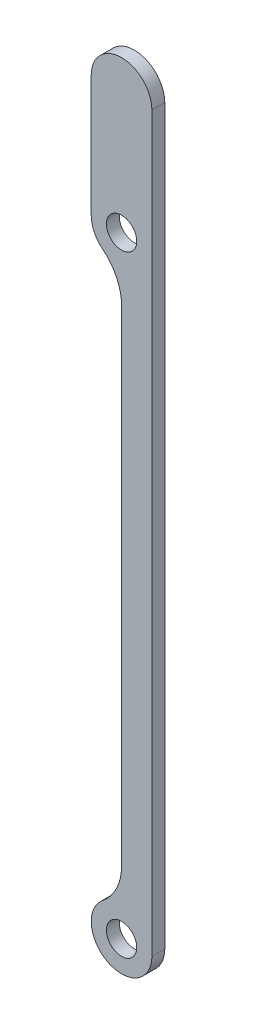
SolidWorks part; units mm, degrees
ref_plane "Front Plane" through (0, 0, 0) normal (0, 0, 1) x (1, 0, 0)
ref_plane "Top Plane" through (0, 0, 0) normal (0, 1, 0) x (1, 0, 0)
ref_plane "Right Plane" through (0, 0, 0) normal (1, 0, 0) x (0, 0, -1)
sketch "Model" plane through (0, 0, 0) normal (0, 0, 1) x (1, 0, 0)
  line L0 (6, 120) -> (6, 145)
  line L1 (0, 12.49) -> (0, 108.51)
  line L4 (6, 120) -> (6, 0)
  line L5 (-6, 145) -> (-6, 121)
  circle A0 centre (0, 0) radius 3
  arc A1 (6, 145) -> (-6, 145) centre (0, 145) ccw
  arc A2 (0, 12.49) -> (-3.75, 4.6837) centre (-10, 12.49) cw
  arc A3 (-3.75, 4.6837) -> (6, 0) centre (0, 0) ccw
  circle A6 centre (0, 121) radius 3
  arc A9 (-3.75, 116.3163) -> (0, 108.51) centre (-10, 108.51) cw
  arc A10 (-6, 121) -> (-3.75, 116.3163) centre (0, 121) ccw
  point P4 (0, 6)
  point P23 (4, 116.5279)
  dimension "D1" = 6
  dimension "D2" = 6
  dimension "D15" = 6
  dimension "D5" = 25
  dimension "D8" = 6
  dimension "D3" = 10
  dimension "D4" = 6
  dimension "D6" = 0
  dimension "D7" = 145
  dimension "D16" = 121
extrude "Boss-Extrude1" add sketch "Model" along normal blind 2.55
